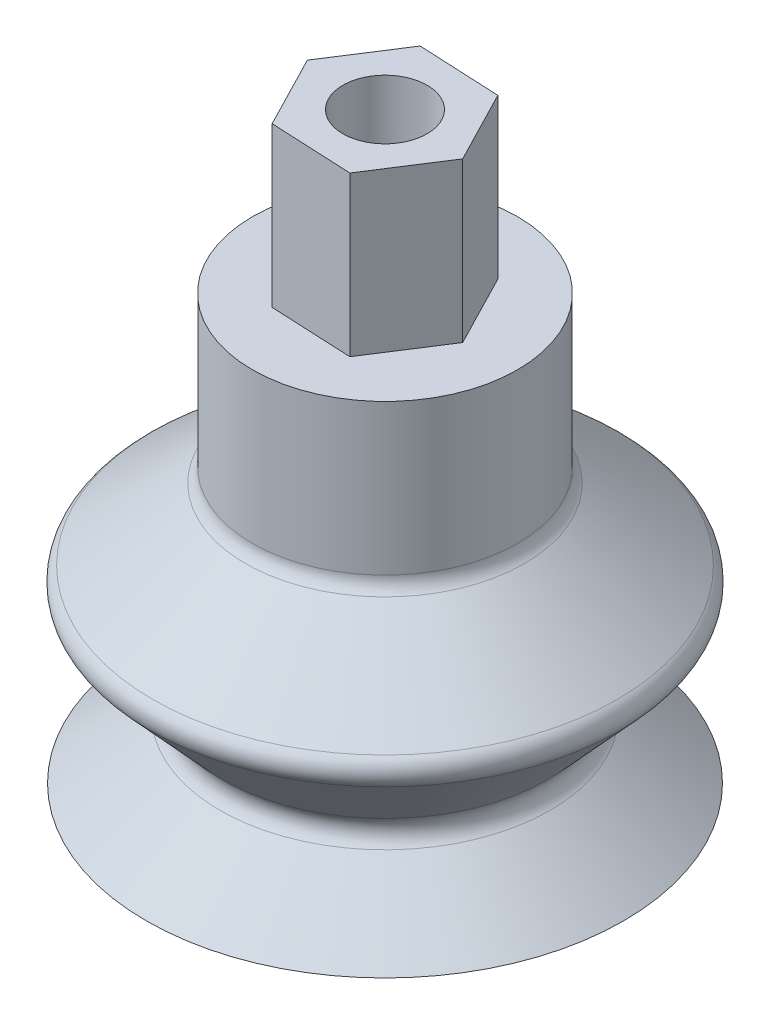
SolidWorks part; units mm, degrees
ref_plane "Front" through (0, 0, 0) normal (0, 0, 1) x (1, 0, 0)
ref_plane "Top" through (0, 0, 0) normal (0, 1, 0) x (1, 0, 0)
ref_plane "Right" through (0, 0, 0) normal (1, 0, 0) x (0, 0, -1)
sketch "Esboço1" plane through (0, 0, 0) normal (0, 0, 1) x (1, 0, 0)
  line L0 (0, 0) -> (13.5, 0)
  line L1 (13.5, 0) -> (8.5, 4)
  line L2 (8.5, 4) -> (14, 10)
  line L3 (14, 10) -> (7.5, 15)
  line L4 (7.5, 15) -> (7.5, 24)
  line L5 (7.5, 24) -> (0, 24)
  line L6 (0, 24) -> (0, 0)
  dimension "D1" = 13.5
  dimension "D2" = 7.5
  dimension "D3" = 14
  dimension "D4" = 8.5
  dimension "D5" = 4
  dimension "D6" = 6
  dimension "D7" = 24
  dimension "D8" = 9
revolve "Revolução1" add sketch "Esboço1" angle 360 about L6
shell "Casca1" thickness 0.9
sketch "Esboço2" plane through (0, 24, 0) normal (0, 1, 0) x (1, 0, 0)
  line L1 (2.4968, 3.8858) -> (-2.1168, 4.1052)
  line L2 (-2.1168, 4.1052) -> (-4.6136, 0.2194)
  line L3 (-4.6136, 0.2194) -> (-2.4968, -3.8858)
  line L4 (-2.4968, -3.8858) -> (2.1168, -4.1052)
  line L5 (2.1168, -4.1052) -> (4.6136, -0.2194)
  line L6 (4.6136, -0.2194) -> (2.4968, 3.8858)
  circle A0 centre (0, 0) radius 4 construction
  dimension "D1" = 8
extrude "Ressalto-extrusão1" add sketch "Esboço2" along normal blind 9
sketch "Esboço3" plane through (0, 33, 0) normal (0, 1, 0) x (1, 0, 0)
  circle A0 centre (0, 0) radius 2.3813
  dimension "D1" = 4.7625
fillet "Filete1" radius 1 3 edges at (-7.5, 15, 0) (-14, 10, 0) (-8.5, 4, 0)
extrude "Corte-extrusão1" cut sketch "Esboço3" against normal through all contours A0
scale "Scale1" scale about origin uniform scaling yes scale factor 1.036484
